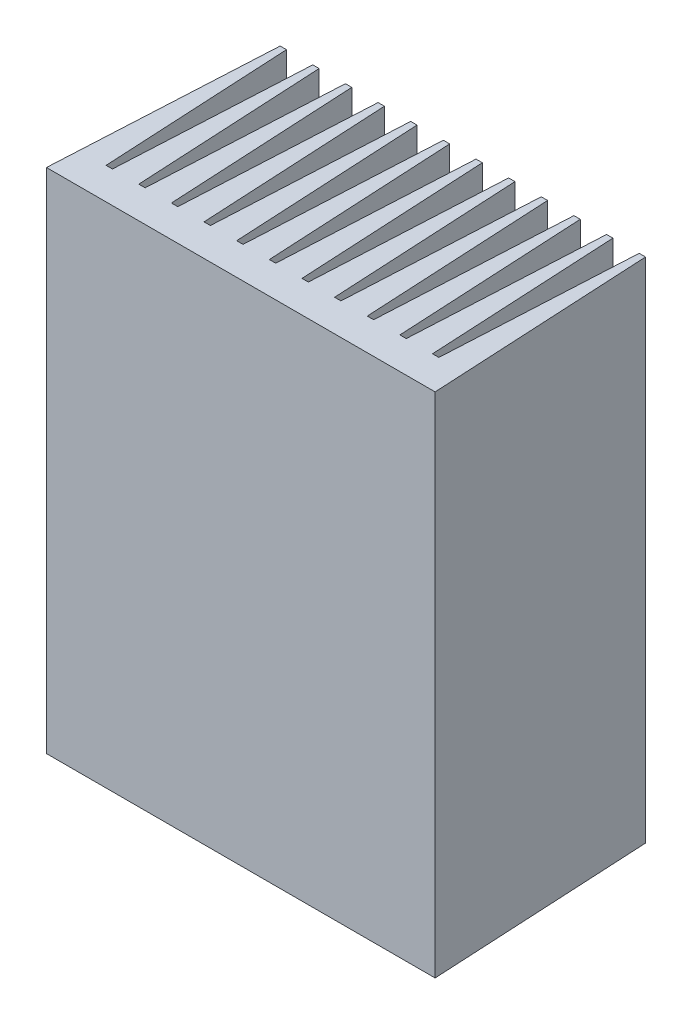
SolidWorks part; units mm, degrees
ref_plane "Front Plane" through (0, 0, 0) normal (0, 0, 1) x (1, 0, 0)
ref_plane "Top Plane" through (0, 0, 0) normal (0, 1, 0) x (1, 0, 0)
ref_plane "Right Plane" through (0, 0, 0) normal (1, 0, 0) x (0, 0, -1)
sketch "Sketch1" plane through (0, 0, 0) normal (0, 1, 0) x (1, 0, 0)
  line L0 (0, 0) -> (0.5, 0)
  line L1 (0.5, 0) -> (2.0722, 30)
  line L2 (2.0722, 30) -> (3.0722, 30)
  line L3 (3.0722, 30) -> (4.6445, 0)
  line L4 (4.6445, 0) -> (5.1445, 0)
  line L5 (-4.159, 30) -> (12.0295, 30) construction
  line L6 (5.1445, 0) -> (5.6445, 0)
  line L7 (5.6445, 0) -> (7.2167, 30)
  line L8 (7.2167, 30) -> (8.2167, 30)
  line L9 (8.2167, 30) -> (9.7889, 0)
  line L10 (9.7889, 0) -> (10.2889, 0)
  line L11 (10.2889, 0) -> (10.7889, 0)
  line L12 (10.7889, 0) -> (12.3612, 30)
  line L13 (12.3612, 30) -> (13.3612, 30)
  line L14 (13.3612, 30) -> (14.9334, 0)
  line L15 (14.9334, 0) -> (15.4334, 0)
  line L16 (15.4334, 0) -> (15.9334, 0)
  line L17 (15.9334, 0) -> (17.5056, 30)
  line L18 (17.5056, 30) -> (18.5056, 30)
  line L19 (18.5056, 30) -> (20.0779, 0)
  line L20 (20.0779, 0) -> (20.5779, 0)
  line L21 (20.5779, 0) -> (21.0779, 0)
  line L22 (21.0779, 0) -> (22.6501, 30)
  line L23 (22.6501, 30) -> (23.6501, 30)
  line L24 (23.6501, 30) -> (25.2223, 0)
  line L25 (25.2223, 0) -> (25.7223, 0)
  line L26 (25.7223, 0) -> (26.2223, 0)
  line L27 (26.2223, 0) -> (27.7946, 30)
  line L28 (27.7946, 30) -> (28.7946, 30)
  line L29 (28.7946, 30) -> (30.6288, -5)
  line L30 (0, -5) -> (30.6288, -5)
  line L31 (0, 0) -> (0, -5)
  line L32 (0, -12.4413) -> (0, 3.9157) construction
  line L33 (30.3668, 0) -> (30.8668, 0) [skipped]
  line L34 (0, 0) -> (0, -5)
  line L35 (0, 0) -> (-0.5, 0)
  line L36 (-0.5, 0) -> (-2.0722, 30)
  line L37 (-2.0722, 30) -> (-3.0722, 30)
  line L38 (-3.0722, 30) -> (-4.6445, 0)
  line L39 (-4.6445, 0) -> (-5.1445, 0)
  line L40 (-5.1445, 0) -> (-5.6445, 0)
  line L41 (-5.6445, 0) -> (-7.2167, 30)
  line L42 (-7.2167, 30) -> (-8.2167, 30)
  line L43 (-8.2167, 30) -> (-9.7889, 0)
  line L44 (-9.7889, 0) -> (-10.2889, 0)
  line L45 (-10.2889, 0) -> (-10.7889, 0)
  line L46 (-10.7889, 0) -> (-12.3612, 30)
  line L47 (-12.3612, 30) -> (-13.3612, 30)
  line L48 (-13.3612, 30) -> (-14.9334, 0)
  line L49 (-14.9334, 0) -> (-15.4334, 0)
  line L50 (-15.4334, 0) -> (-15.9334, 0)
  line L51 (-15.9334, 0) -> (-17.5056, 30)
  line L52 (-17.5056, 30) -> (-18.5056, 30)
  line L53 (-18.5056, 30) -> (-20.0779, 0)
  line L54 (-20.0779, 0) -> (-20.5779, 0)
  line L55 (-20.5779, 0) -> (-21.0779, 0)
  line L56 (-21.0779, 0) -> (-22.6501, 30)
  line L57 (-22.6501, 30) -> (-23.6501, 30)
  line L58 (-23.6501, 30) -> (-25.2223, 0)
  line L59 (-25.2223, 0) -> (-25.7223, 0)
  line L60 (-25.7223, 0) -> (-26.2223, 0)
  line L61 (-26.2223, 0) -> (-27.7946, 30)
  line L62 (-27.7946, 30) -> (-28.7946, 30)
  line L63 (-28.7946, 30) -> (-30.6288, -5)
  line L64 (0, -5) -> (-30.6288, -5)
  point P69 (0, 0)
  dimension "D1" = 0.5
  dimension "D2" = 0.5
  dimension "D3" = 1
  dimension "D4" = 35
  dimension "D5" = 87
  dimension "D6" = 87
  dimension "D7" = 6
  dimension "D8" = 0.5
  dimension "D9" = 5
extrude "Boss-Extrude2" add sketch "Sketch1" along normal blind 80 contours L64 L31 L35 L36 L37 L38 L39 L40 L41 L42 L43 L44 L45 L46 L47 L48 L49 L50 L51 L52 L53 L54 L55 L56 L57 L58 L59 L60 L61 L62 L63 | L0 L31 L30 L29 L28 L27 L26 L25 L24 L23 L22 L21 L20 L19 L18 L17 L16 L15 L14 L13 L12 L11 L10 L9 L8 L7 L6 L4 L3 L2 L1
